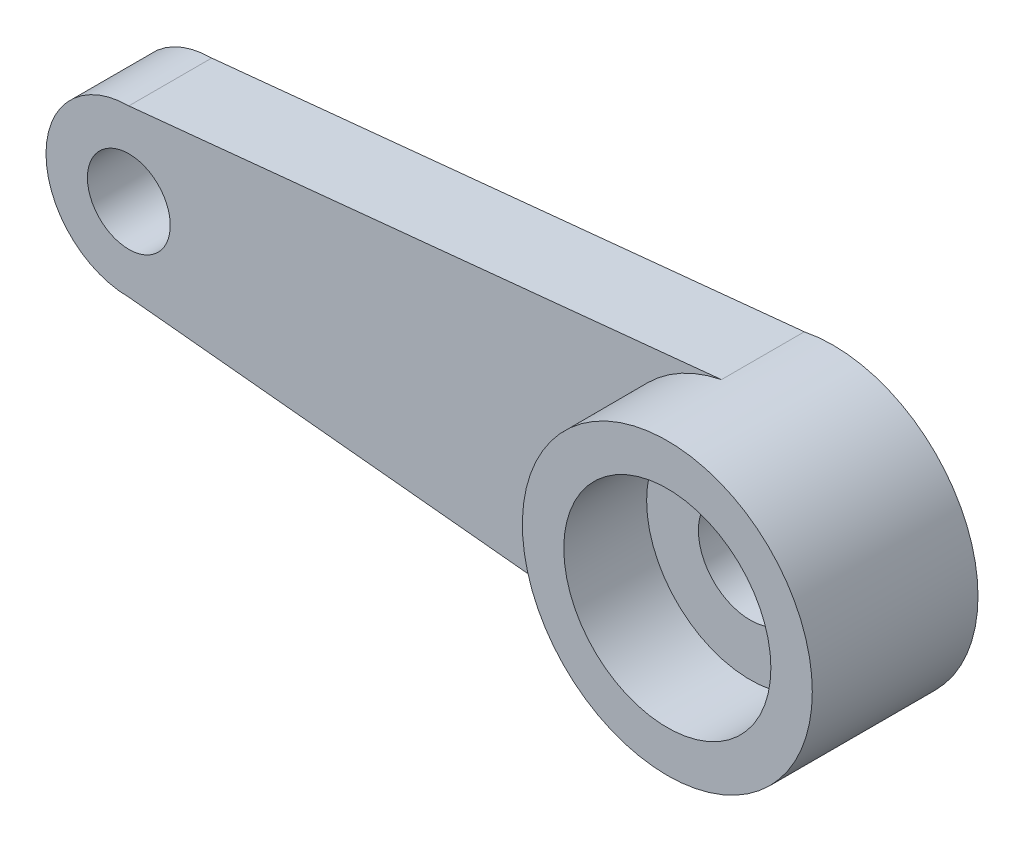
SolidWorks part; units mm, degrees
material "ABS"
ref_plane "Front Plane" through (0, 0, 0) normal (0, 0, 1) x (1, 0, 0)
ref_plane "Top Plane" through (0, 0, 0) normal (0, 1, 0) x (1, 0, 0)
ref_plane "Right Plane" through (0, 0, 0) normal (1, 0, 0) x (0, 0, -1)
sketch "Sketch1" plane through (0, 0, 0) normal (0, 0, 1) x (1, 0, 0)
  circle A0 centre (0, 0) radius 3.5
  circle A1 centre (0, 0) radius 2.5
  dimension "D1" = 7
  dimension "D2" = 5
extrude "Boss-Extrude1" add sketch "Sketch1" along normal blind 4
sketch "Sketch2" plane through (0, 0, 0) normal (0, 0, -1) x (-1, 0, 0)
  line L0 (0, 3.5) -> (15, 2)
  line L1 (0, -3.5) -> (15, -2)
  arc A0 (15, -2) -> (15, 2) centre (15, 0) ccw
  circle A1 centre (0, 0) radius 3.5 construction
  arc A2 (0, 3.5) -> (0, -3.5) centre (0, 0) cw
  circle A3 centre (15, 0) radius 1
  circle M1 centre (0, 0) radius 3.5
  dimension "D1" = 4
  dimension "D3" = 2
  dimension "D2" = 15
extrude "Boss-Extrude2" add sketch "Sketch2" against normal blind 2 contours L1 A0 L0 A3 M1
sketch "Sketch3" plane through (0, 0, 0) normal (0, 0, -1) x (-1, 0, 0)
  circle A0 centre (0, 0) radius 1.25
  circle A1 centre (0, 0) radius 2.5
  dimension "D1" = 2.5
  dimension "D2" = 5
extrude "Boss-Extrude3" add sketch "Sketch3" against normal blind 2
